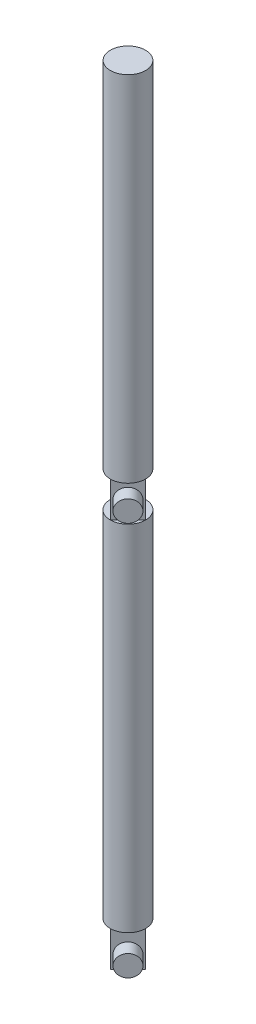
SolidWorks part; units mm, degrees
ref_plane "Front Plane" through (0, 0, 0) normal (0, 0, 1) x (1, 0, 0)
ref_plane "Top Plane" through (0, 0, 0) normal (0, 1, 0) x (1, 0, 0)
ref_plane "Right Plane" through (0, 0, 0) normal (1, 0, 0) x (0, 0, -1)
sketch "Sketch1" plane through (0, 0, 0) normal (0, 1, 0) x (1, 0, 0)
  circle A0 centre (-21.9966, 2.2231) radius 25
extrude "Boss-Extrude1" add sketch "Sketch1" along normal blind 500
sketch "Sketch3" plane through (0, 500, 0) normal (0, 1, 0) x (1, 0, 0)
  line L0 (-46.9966, 2.2231) -> (-21.9966, -22.7769)
  line L1 (-46.9966, 2.2231) -> (-22.0554, 27.1643)
  line L2 (-21.9966, -22.7769) -> (2.9446, 2.1643)
  line L3 (-22.0554, 27.1643) -> (2.9446, 2.1643)
  circle A0 centre (-21.9966, 2.2231) radius 25 construction
extrude "Boss-Extrude2" add sketch "Sketch3" along normal blind 50
sketch "Sketch4" plane through (0, 0, 0) normal (0, -1, 0) x (-1, 0, 0)
  line L0 (46.9966, 2.2231) -> (21.9966, 27.2231)
  line L1 (46.9966, 2.2231) -> (21.9897, -22.7839)
  line L2 (21.9966, 27.2231) -> (-3.0103, 2.2161)
  line L3 (21.9897, -22.7839) -> (-3.0103, 2.2161)
  circle A0 centre (21.9966, 2.2231) radius 25 construction
extrude "Boss-Extrude3" add sketch "Sketch4" along normal blind 50
sketch "Sketch5" plane through (0.3971, 0, 0.3971) normal (0.7071, 0, 0.7071) x (0.7071, 0, -0.7071)
  circle A1 centre (-13.9815, -31.4) radius 15
  circle A2 centre (-14.0236, 525) radius 15
  dimension "D1" = 556.4
extrude "Boss-Extrude5" add sketch "Sketch5" along normal blind 20 and the other way blind 55.4
sketch "Sketch8" plane through (0, 550, 0) normal (0, 1, 0) x (1, 0, 0)
  circle A0 centre (-21.9966, 2.2231) radius 24.8782
extrude "Boss-Extrude6" add sketch "Sketch8" along normal blind 500
